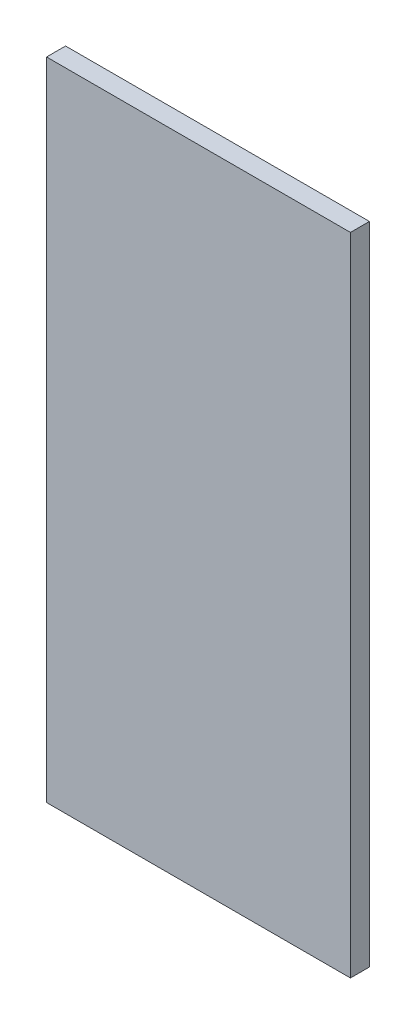
SolidWorks part; units mm, degrees
ref_plane "Alzado" through (0, 0, 0) normal (0, 0, 1) x (1, 0, 0)
ref_plane "Planta" through (0, 0, 0) normal (0, 1, 0) x (1, 0, 0)
ref_plane "Vista lateral" through (0, 0, 0) normal (1, 0, 0) x (0, 0, -1)
sketch "Croquis1" plane through (0, 0, 0) normal (0, 0, 1) x (1, 0, 0)
  line L1 (20, -42.5) -> (-20, -42.5)
  line L2 (20, -42.5) -> (20, 42.5)
  line L3 (20, 42.5) -> (-20, 42.5)
  line L4 (-20, -42.5) -> (-20, 42.5)
  line L5 (20, -42.5) -> (-20, 42.5) construction
  line L6 (20, 42.5) -> (-20, -42.5) construction
  point P0 (0, 0)
  dimension "D1" = 40
  dimension "D2" = 85
extrude "Saliente-Extruir1" add sketch "Croquis1" along normal blind 2.5
